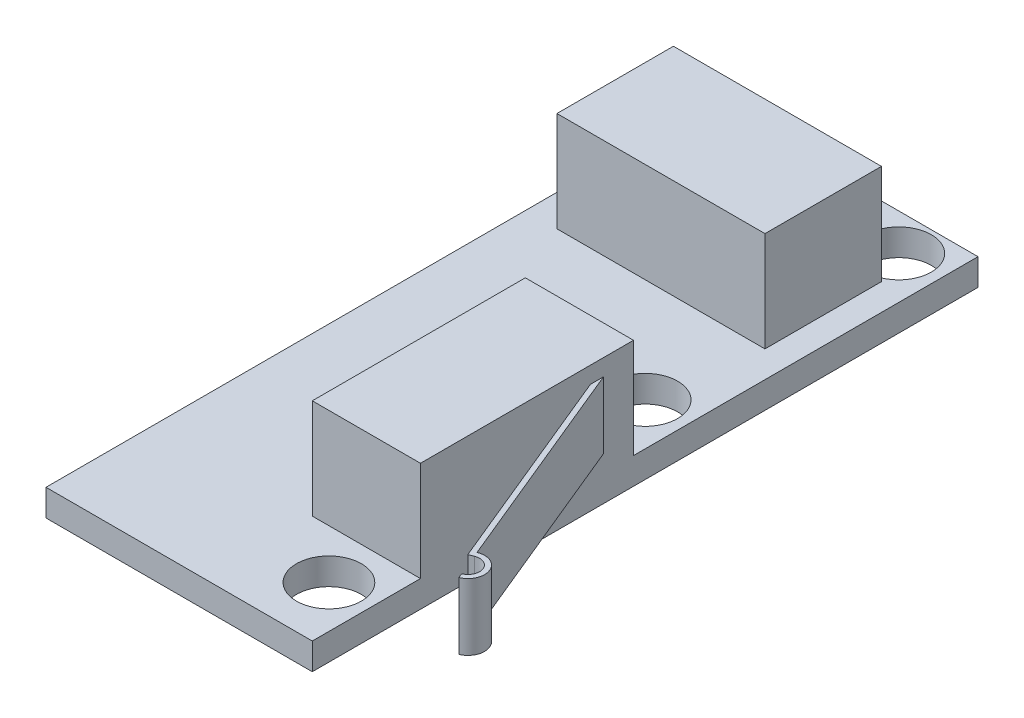
SolidWorks part; units mm, degrees
ref_plane "Front Plane" through (0, 0, 0) normal (0, 0, 1) x (1, 0, 0)
ref_plane "Top Plane" through (0, 0, 0) normal (0, 1, 0) x (1, 0, 0)
ref_plane "Right Plane" through (0, 0, 0) normal (1, 0, 0) x (0, 0, -1)
sketch "Sketch1" plane through (0, 0, 0) normal (0, 1, 0) x (1, 0, 0)
  line L1 (0, 0) -> (16, 0)
  line L2 (0, 0) -> (0, 40)
  line L3 (0, 40) -> (16, 40)
  line L4 (16, 0) -> (16, 40)
  dimension "D1" = 16
  dimension "D2" = 40
extrude "Boss-Extrude1" add sketch "Sketch1" along normal blind 1.6
sketch "Sketch2" plane through (0, 1.6, 0) normal (0, 1, 0) x (1, 0, 0)
  line L0 (0, 40) -> (0, 0) construction
  line L3 (0, 0) -> (16, 0) construction
  circle A0 centre (2.55, 37.7922) radius 1.95
  circle A1 centre (13.45, 37.7922) radius 1.95
  circle A2 centre (13.45, 3.55) radius 1.95
  circle A3 centre (13.45, 22.55) radius 1.95
  dimension "D2" = 3.9
  dimension "D1" = 10.9
  dimension "D4" = 2.55
  dimension "D5" = 3.55
  dimension "D6" = 22.55
extrude "Cut-Extrude1" cut sketch "Sketch2" against normal blind 1.6
sketch "Sketch3" plane through (0, 1.6, 0) normal (0, 1, 0) x (1, 0, 0)
  line L0 (16, 0) -> (16, 40) construction
  line L1 (1.9, 35.8) -> (14.4, 35.8)
  line L2 (1.9, 35.8) -> (1.9, 28.8)
  line L3 (1.9, 28.8) -> (14.4, 28.8)
  line L4 (14.4, 35.8) -> (14.4, 28.8)
  line L6 (16, 40) -> (0, 40) construction
  line L8 (9.5, 19.3) -> (16, 19.3)
  line L9 (9.5, 19.3) -> (9.5, 6.5)
  line L10 (9.5, 6.5) -> (16, 6.5)
  line L11 (16, 19.3) -> (16, 6.5)
  line L12 (0, 0) -> (16, 0) construction
  point P4 (1.9, 32.3)
  point P13 (16, 20)
  point P15 (12.75, 6.5)
  dimension "D1" = 12.5
  dimension "D2" = 1.6
  dimension "D3" = 7
  dimension "D4" = 4.2
  dimension "D5" = 12.8
  dimension "D6" = 6.5
  dimension "D7" = 6.5
extrude "Boss-Extrude2" add sketch "Sketch3" along normal blind 6
sketch "Sketch4" plane through (0.7601, 7.6, -17.343) normal (0, -1, 0) x (1, 0, 0)
  line L6 (15.2399, -1.957) -> (8.7399, -1.957) construction
  line L7 (15.2399, 10.843) -> (15.2399, -1.957) construction
  line L12 (15.2399, -0.157) -> (20.5794, 12.7847)
  line L13 (15.2399, 0.6295) -> (15.2399, -0.157)
  line L17 (21.2278, 14.3562) -> (21.3422, 14.6336)
  line L18 (20.6938, 13.0621) -> (20.4165, 13.1766)
  line L19 (20.4165, 13.1766) -> (15.2399, 0.6295)
  arc A0 (20.5794, 12.7847) -> (21.3422, 14.6336) centre (20.9608, 13.7092) ccw
  arc A1 (20.6938, 13.0621) -> (21.2278, 14.3562) centre (20.9608, 13.7092) ccw
  dimension "D5" = 2
  dimension "D1" = 1.8
  dimension "D4" = 16
  dimension "D6" = 0.3
extrude "Boss-Extrude3" add sketch "Sketch4" along normal blind 4 from offset 1 contours L19 L13 L12 A0 L17 A1 L18
